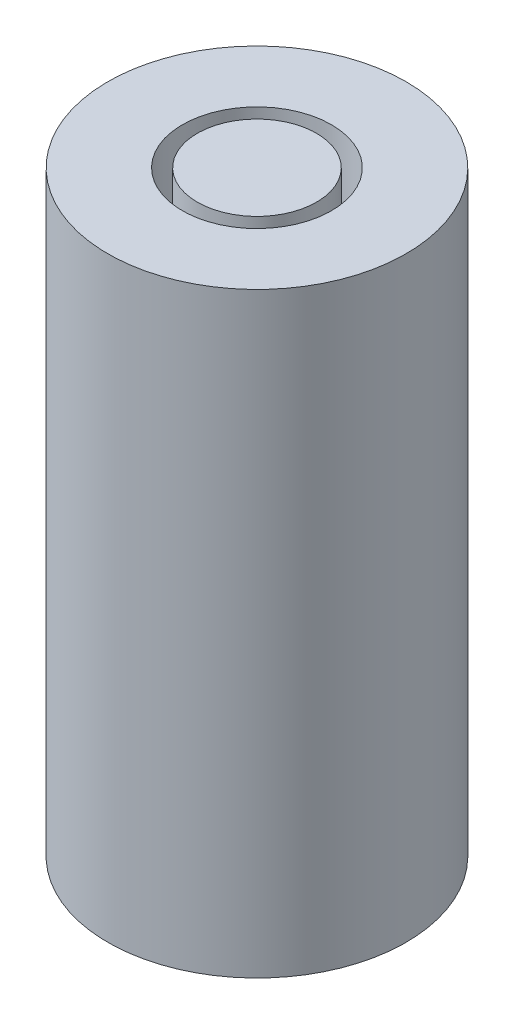
SolidWorks part; units mm, degrees
ref_plane "Front Plane" through (0, 0, 0) normal (0, 0, 1) x (1, 0, 0)
ref_plane "Top Plane" through (0, 0, 0) normal (0, 1, 0) x (1, 0, 0)
ref_plane "Right Plane" through (0, 0, 0) normal (1, 0, 0) x (0, 0, -1)
sketch "Sketch1" plane through (0, 0, 0) normal (0, 1, 0) x (1, 0, 0)
  circle A0 centre (0, 0) radius 1
  dimension "D1" = 2
extrude "Boss-Extrude1" add sketch "Sketch1" along normal blind 10
sketch "Sketch2" plane through (0, 0, 0) normal (0, -1, 0) x (1, 0, 0)
  circle A0 centre (0, 0) radius 1.25
  circle A1 centre (0, 0) radius 2.5
  dimension "D1" = 2.5
  dimension "D2" = 5
extrude "Boss-Extrude2" add sketch "Sketch2" against normal blind 10 separate body
